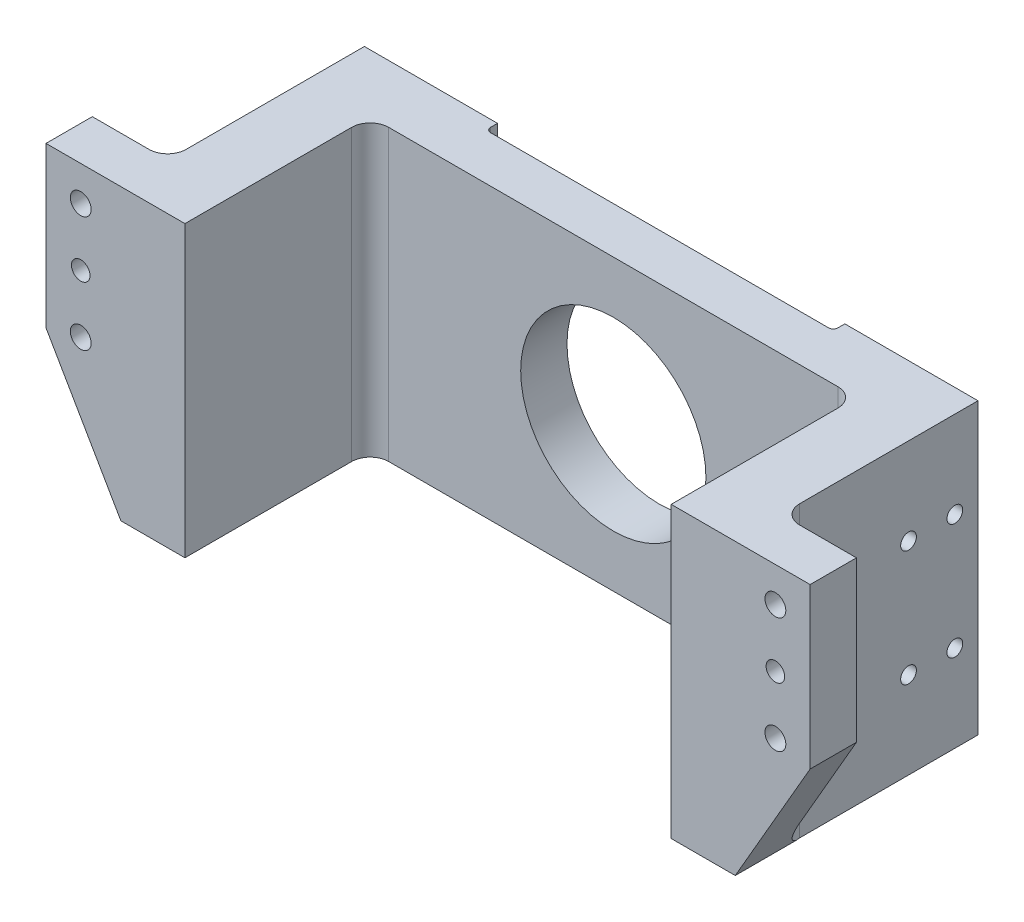
SolidWorks part; units mm, degrees
material "Q235"
ref_plane "前视基准面" through (0, 0, 0) normal (0, 0, 1) x (1, 0, 0)
ref_plane "上视基准面" through (0, 0, 0) normal (0, 1, 0) x (1, 0, 0)
ref_plane "右视基准面" through (0, 0, 0) normal (1, 0, 0) x (0, 0, -1)
sketch "草图1" plane through (0, 0, 0) normal (0, 0, 1) x (1, 0, 0)
  line L1 (-132.5, -62.5) -> (132.5, -62.5)
  line L2 (-132.5, -62.5) -> (-132.5, 62.5)
  line L3 (-132.5, 62.5) -> (132.5, 62.5)
  line L4 (132.5, -62.5) -> (132.5, 62.5)
  line L5 (-132.5, -62.5) -> (132.5, 62.5) construction
  line L6 (-132.5, 62.5) -> (132.5, -62.5) construction
  point P0 (0, 0)
  dimension "D1" = 265
  dimension "D2" = 125
extrude "凸台-拉伸1" add sketch "草图1" along normal blind 85
sketch "草图2" plane through (0, 0, 85) normal (0, 0, 1) x (1, 0, 0)
  line L0 (132.5, 62.5) -> (-132.5, 62.5) construction
  line L1 (-165, -62.5) -> (165, -62.5)
  line L2 (-165, -62.5) -> (-165, 62.5)
  line L3 (-165, 62.5) -> (165, 62.5)
  line L4 (165, -62.5) -> (165, 62.5)
  line L5 (-165, -62.5) -> (165, 62.5) construction
  line L6 (-165, 62.5) -> (165, -62.5) construction
  point P0 (0, 0)
  dimension "D1" = 330
extrude "凸台-拉伸2" add sketch "草图2" along normal blind 20
sketch "草图3" plane through (0, 0, 0) normal (0, 0, -1) x (-1, 0, 0)
  line L0 (132.5, -62.5) -> (-132.5, -62.5) construction
  line L1 (75, 62.5) -> (-75, 62.5)
  line L2 (75, 62.5) -> (75, -62.5)
  line L3 (75, -62.5) -> (-75, -62.5)
  line L4 (-75, 62.5) -> (-75, -62.5)
  line L5 (75, 62.5) -> (-75, -62.5) construction
  line L6 (75, -62.5) -> (-75, 62.5) construction
  point P0 (0, 0)
  dimension "D1" = 150
extrude "切除-拉伸1" cut sketch "草图3" against normal blind 5
sketch "草图4" plane through (0, 0, 0) normal (0, 0, -1) x (-1, 0, 0)
  circle A0 centre (0, 0) radius 40
  dimension "D1" = 80
extrude "切除-拉伸2" cut sketch "草图4" against normal through all
sketch "草图5" plane through (0, 0, 105) normal (0, 0, 1) x (1, 0, 0)
  line L0 (165, 62.5) -> (-165, 62.5) construction
  line L1 (-105, -62.5) -> (105, -62.5)
  line L2 (-105, -62.5) -> (-105, 62.5)
  line L3 (-105, 62.5) -> (105, 62.5)
  line L4 (105, -62.5) -> (105, 62.5)
  line L5 (-105, -62.5) -> (105, 62.5) construction
  line L6 (-105, 62.5) -> (105, -62.5) construction
  point P0 (0, 0)
  dimension "D1" = 210
extrude "切除-拉伸3" cut sketch "草图5" against normal blind 80
chamfer "倒角2" distance 56 angle 30 2 edges at (165, -62.5, 95) (-165, -62.5, 95)
sketch "草图10" plane through (0, 0, 85) normal (0, 0, -1) x (-1, 0, 0)
  line L0 (-150, 50) -> (-150, 45) construction
  line L1 (132.5, 62.5) -> (165, 62.5) construction
  line L2 (-154.5, 50) -> (-154.5, 45) construction
  line L3 (-165, 22.5) -> (165, 22.5) construction
  line L4 (-145.5, 50) -> (-145.5, 45) construction
  line L5 (-165, -6.5) -> (-165, 62.5) construction
  line L6 (-150, 47.5) -> (-150, -2.5) construction
  line L8 (-150, -5) -> (-150, 0) construction
  line L9 (-145.5, -5) -> (-145.5, 0) construction
  line L10 (-154.5, -5) -> (-154.5, 0) construction
  arc A0 (-145.5, 50) -> (-154.5, 50) centre (-150, 50) ccw construction
  arc A1 (-154.5, 45) -> (-145.5, 45) centre (-150, 45) ccw construction
  arc A2 (-154.5, 0) -> (-145.5, 0) centre (-150, 0) cw construction
  arc A3 (-145.5, -5) -> (-154.5, -5) centre (-150, -5) cw construction
  circle A4 centre (-150, 47.5) radius 4.5
  circle A5 centre (-150, -2.5) radius 4.5
  circle A6 centre (-150, 22.5) radius 4
  point P12 (-150, 47.5)
  point P19 (-150, -2.5)
  dimension "D1" = 9
  dimension "D5" = 8
  dimension "D2" = 15
  dimension "D3" = 25
  dimension "D4" = 5
  dimension "D6" = 40
extrude "切除-拉伸4" cut sketch "草图10" against normal through all
hole_wizard "M16 螺纹孔1" positions "草图9" profile "草图8" tap size "M16" standard "GB"
sketch "草图9" plane through (0, 0, 0) normal (0, 0, -1) x (-1, 0, 0)
  line L0 (-102.5, 0) -> (-107.5, 0) construction
  line L2 (107.5, 0) -> (102.5, 0) construction
  point P0 (105, 0)
  point P1 (-105, 0)
sketch "草图8" plane through (-105, 0, 0) normal (1, 0, 0) x (0, 1, 0)
  line L0 (0, 0) -> (0, 24.206)
  line L1 (0, 24.206) -> (7, 20)
  line L2 (7, 20) -> (7, 0)
  line L5 (7, 0) -> (0, 0)
  line L10 (0, 24.206) -> (-7, 20) construction
  line L11 (0, -6.35) -> (0, 107.95) construction
  dimension "螺纹孔钻头直径" = 14
  dimension "螺纹孔钻头深度" = 20
  dimension "导头角度" = 118
cosmetic thread "孔螺蚊线1" parameters "D1"=32, "D2"=16
cosmetic thread "孔螺蚊线2" parameters "D1"=32, "D2"=16
ref_plane "基准面1" through (0, 0, 0) normal (-1, 0, 0) x (0, 0, 1)
mirror "镜向1" about plane through (0, 0, 0) normal (-1, 0, 0) of "切除-拉伸4"
chamfer "倒角3" distance 1 angle 45 2 edges at (-146, 22.5, 85) (146, 22.5, 85)
hole_wizard "打孔尺寸根据内六角圆柱头螺钉的类型1" positions "草图12" profile "草图11" counterbore size "M8" standard "GB" end condition through all
sketch "草图12" plane through (0, 0, 85) normal (0, 0, -1) x (-1, 0, 0)
  point P0 (150, -2.5)
  point P1 (150, 47.5)
  point P3 (-150, -2.5)
  point P5 (-150, 47.5)
sketch "草图11" plane through (-150, -2.5, 85) normal (1, 0, 0) x (0, 1, 0)
  line L0 (0, 0) -> (0, 20)
  line L1 (0, 20) -> (4.5, 20)
  line L3 (4.5, 20) -> (4.5, 9)
  line L4 (4.5, 9) -> (7.5, 9)
  line L5 (7.5, 9) -> (7.5, 0)
  line L7 (7.5, 0) -> (0, 0)
  line L11 (0, -6.35) -> (0, 107.95) construction
  dimension "通孔孔直径" = 9
  dimension "通孔孔深度" = 20
  dimension "柱形沉头孔直径" = 15
  dimension "柱形沉头孔深度" = 9
hole_wizard "M8 螺纹孔1" positions "草图16" profile "草图15" tap size "M8" standard "GB"
sketch "草图16" plane through (132.5, 0, 0) normal (1, 0, 0) x (0, 0, -1)
  line L1 (-10, 25) -> (-30, 25) construction
  line L2 (-10, 25) -> (-10, -25) construction
  line L3 (-10, -25) -> (-30, -25) construction
  line L4 (-30, 25) -> (-30, -25) construction
  line L5 (0, -62.5) -> (0, 62.5) construction
  line L6 (0, 0) -> (-44.8087, 0) construction
  point P0 (-10, 25)
  point P1 (-30, 25)
  point P3 (-30, -25)
  point P5 (-10, -25)
  dimension "D1" = 10
  dimension "D2" = 20
  dimension "D3" = 50
  dimension "D4" = 25
sketch "草图15" plane through (132.5, 25, 10) normal (0, 1, 0) x (0, 0, -1)
  line L0 (0, 0) -> (0, 24.2929)
  line L1 (0, 24.2929) -> (3.4, 22.25)
  line L2 (3.4, 22.25) -> (3.4, 0)
  line L5 (3.4, 0) -> (0, 0)
  line L10 (0, 24.2929) -> (-3.4, 22.25) construction
  line L11 (0, -6.35) -> (0, 107.95) construction
  dimension "螺纹孔钻头直径" = 6.8
  dimension "螺纹孔钻头深度" = 22.25
  dimension "导头角度" = 118
cosmetic thread "孔螺蚊线3" parameters "D1"=16, "D2"=8
cosmetic thread "孔螺蚊线4" parameters "D1"=16, "D2"=8
cosmetic thread "孔螺蚊线5" parameters "D1"=16, "D2"=8
cosmetic thread "孔螺蚊线6" parameters "D1"=16, "D2"=8
fillet "圆角1" radius 8 4 edges at (105, 0, 25) (-105, 0, 25)
fillet "圆角2" radius 2 2 edges at (-75, 0, 5) (75, 0, 5)
